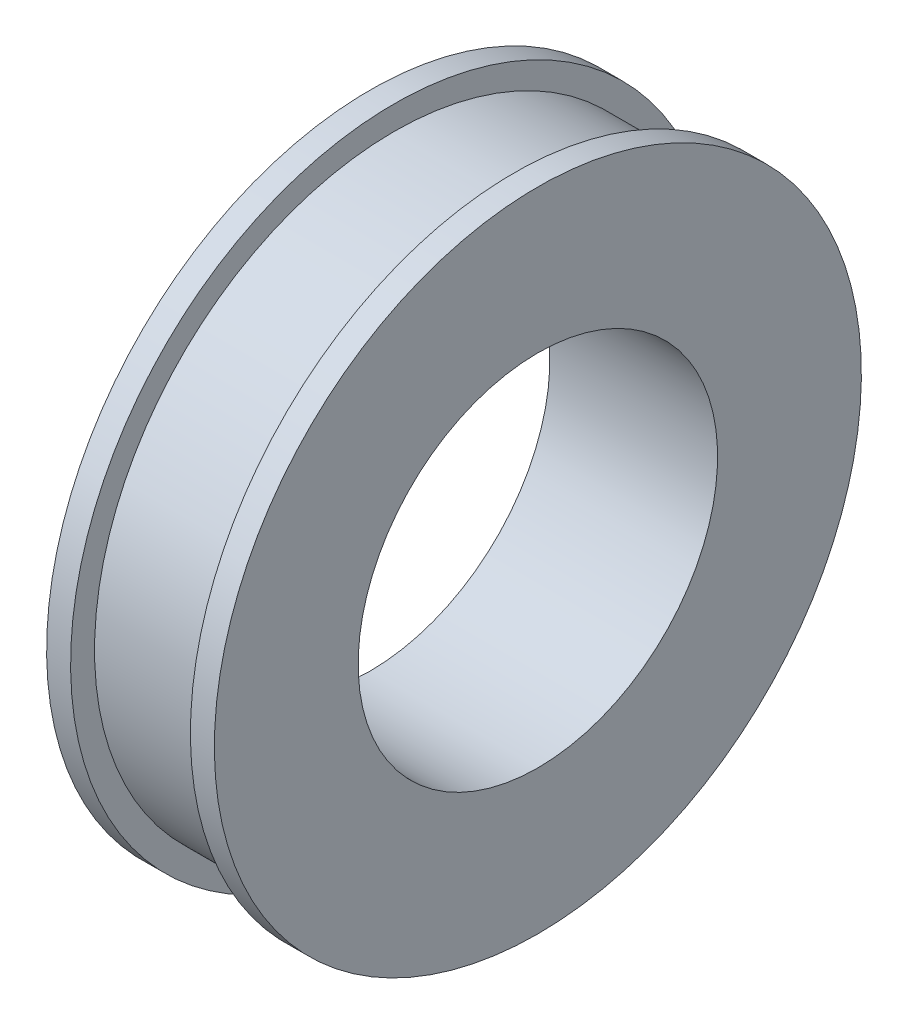
SolidWorks part; units mm, degrees
material "Cast Alloy Steel"
ref_plane "Front Plane" through (0, 0, 0) normal (0, 0, 1) x (1, 0, 0)
ref_plane "Top Plane" through (0, 0, 0) normal (0, 1, 0) x (1, 0, 0)
ref_plane "Right Plane" through (0, 0, 0) normal (1, 0, 0) x (0, 0, -1)
sketch "Sketch1" plane through (0, 0, 0) normal (0, 0, 1) x (1, 0, 0)
  line L0 (-7, 0) -> (7, 0) construction
  line L1 (7, 15) -> (7, 27)
  line L2 (7, 27) -> (5, 27)
  line L3 (5, 27) -> (5, 25)
  line L4 (5, 25) -> (-5, 25)
  line L5 (-5, 25) -> (-5, 27)
  line L6 (-5, 27) -> (-7, 27)
  line L7 (-7, 27) -> (-7, 15)
  line L10 (-7, 15) -> (7, 15)
  point P0 (0, 0)
  point P7 (0, 15)
  point P11 (7, 27)
  point P13 (6.2183, 0)
  point P14 (0, 0)
  dimension "D1" = 15
  dimension "D2" = 2
  dimension "D3" = 10
  dimension "D4" = 27
  dimension "D5" = 25
revolve "Revolve1" add sketch "Sketch1" angle 360 about L0
